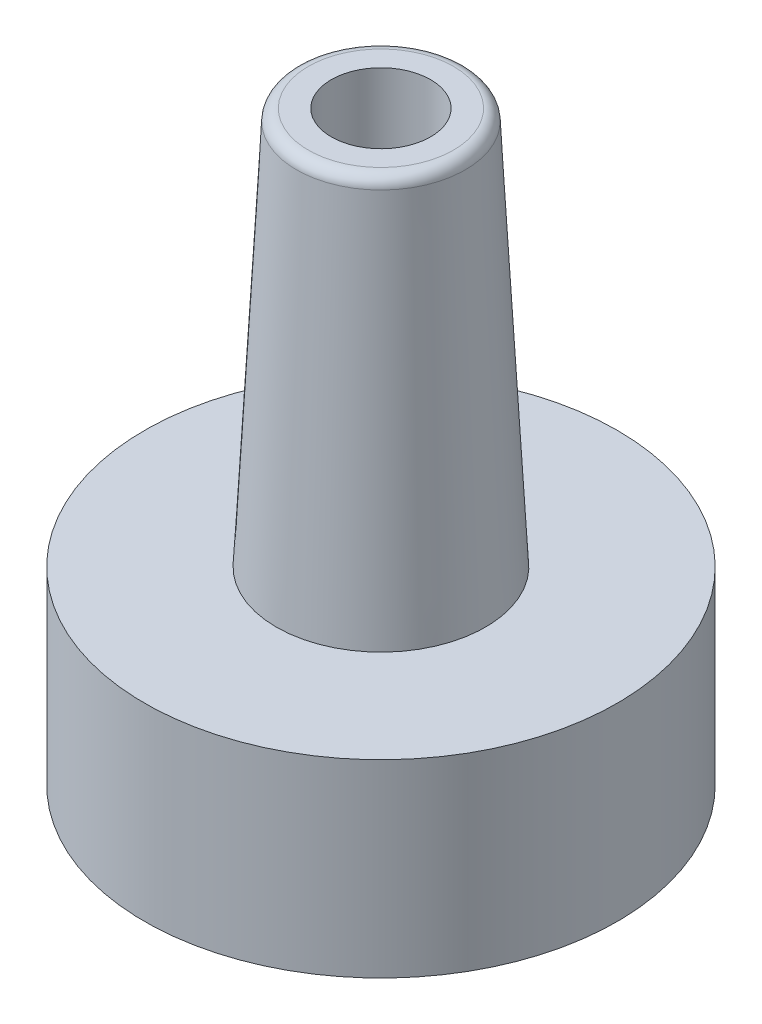
SolidWorks part; units mm, degrees
ref_plane "Front Plane" through (0, 0, 0) normal (0, 0, 1) x (1, 0, 0)
ref_plane "Top Plane" through (0, 0, 0) normal (0, 1, 0) x (1, 0, 0)
ref_plane "Right Plane" through (0, 0, 0) normal (1, 0, 0) x (0, 0, -1)
sketch "Sketch2" plane through (0, 0, 0) normal (0, 0, 1) x (1, 0, 0)
  line L0 (-4.6646, 0) -> (4.5247, 0) construction
  line L1 (-1.05, 0) -> (-2.213, 0)
  line L2 (-1.05, 0) -> (-1.05, 8.4)
  line L3 (0, 0) -> (0, 10.2192) construction
  line L4 (-1.05, 8.4) -> (-1.5355, 8.4)
  line L5 (-1.7852, 8.1631) -> (-2.213, 0)
  arc A0 (-1.5355, 8.4) -> (-1.7852, 8.1631) centre (-1.5355, 8.15) ccw
  dimension "D2" = 0.25
  dimension "D1" = 8.4
  dimension "D3" = 1.05
  dimension "D4" = 2.213
  dimension "D5" = 3
revolve "luer" add sketch "Sketch2" angle 360 about L3
sketch "Sketch3" plane through (0, 0, 0) normal (0, -1, 0) x (1, 0, 0)
  circle A0 centre (0, 0) radius 0.8
  circle A1 centre (0, 0) radius 5
  dimension "D1" = 1.6
  dimension "D2" = 10
extrude "Boss-Extrude1" add sketch "Sketch3" along normal blind 4
